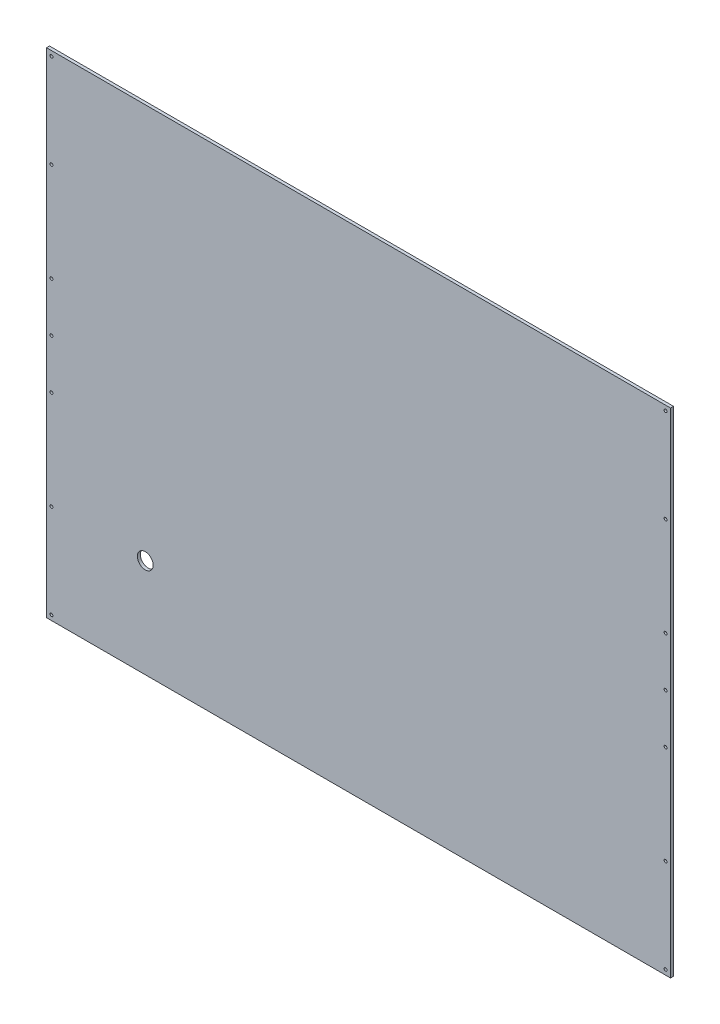
SolidWorks part; units mm, degrees
ref_plane "前视基准面" through (0, 0, 0) normal (0, 0, 1) x (1, 0, 0)
ref_plane "上视基准面" through (0, 0, 0) normal (0, 1, 0) x (1, 0, 0)
ref_plane "右视基准面" through (0, 0, 0) normal (1, 0, 0) x (0, 0, -1)
sketch "草图1" plane through (0, 0, 0) normal (0, 0, 1) x (1, 0, 0)
  line L0 (627, 537.5875) -> (627, -65.4008) construction
  line L1 (0, 0) -> (632, 0)
  line L2 (0, 0) -> (0, 500)
  line L3 (0, 500) -> (632, 500)
  line L4 (632, 0) -> (632, 500)
  line L5 (632, 250) -> (-43.4407, 250) construction
  line L6 (316, 500) -> (316, 184.5786) construction
  circle A0 centre (627, 250) radius 1.5
  circle A1 centre (627, 300) radius 1.5
  circle A3 centre (627, 400) radius 1.5
  circle A5 centre (627, 495) radius 1.5
  circle A6 centre (627, 5) radius 1.5
  circle A7 centre (627, 100) radius 1.5
  circle A8 centre (627, 200) radius 1.5
  circle A9 centre (5, 200) radius 1.5
  circle A10 centre (5, 100) radius 1.5
  circle A11 centre (5, 5) radius 1.5
  circle A12 centre (5, 495) radius 1.5
  circle A13 centre (5, 400) radius 1.5
  circle A14 centre (5, 300) radius 1.5
  circle A15 centre (5, 250) radius 1.5
  circle A16 centre (100, 100) radius 8
  dimension "D4" = 100
  dimension "D8" = 5
  dimension "D6" = 16
  dimension "D1" = 500
  dimension "D2" = 632
  dimension "D3" = 5
  dimension "D5" = 100
  dimension "D7" = 100
  dimension "D9" = 100
extrude "凸台-拉伸1" add sketch "草图1" along normal blind 3
